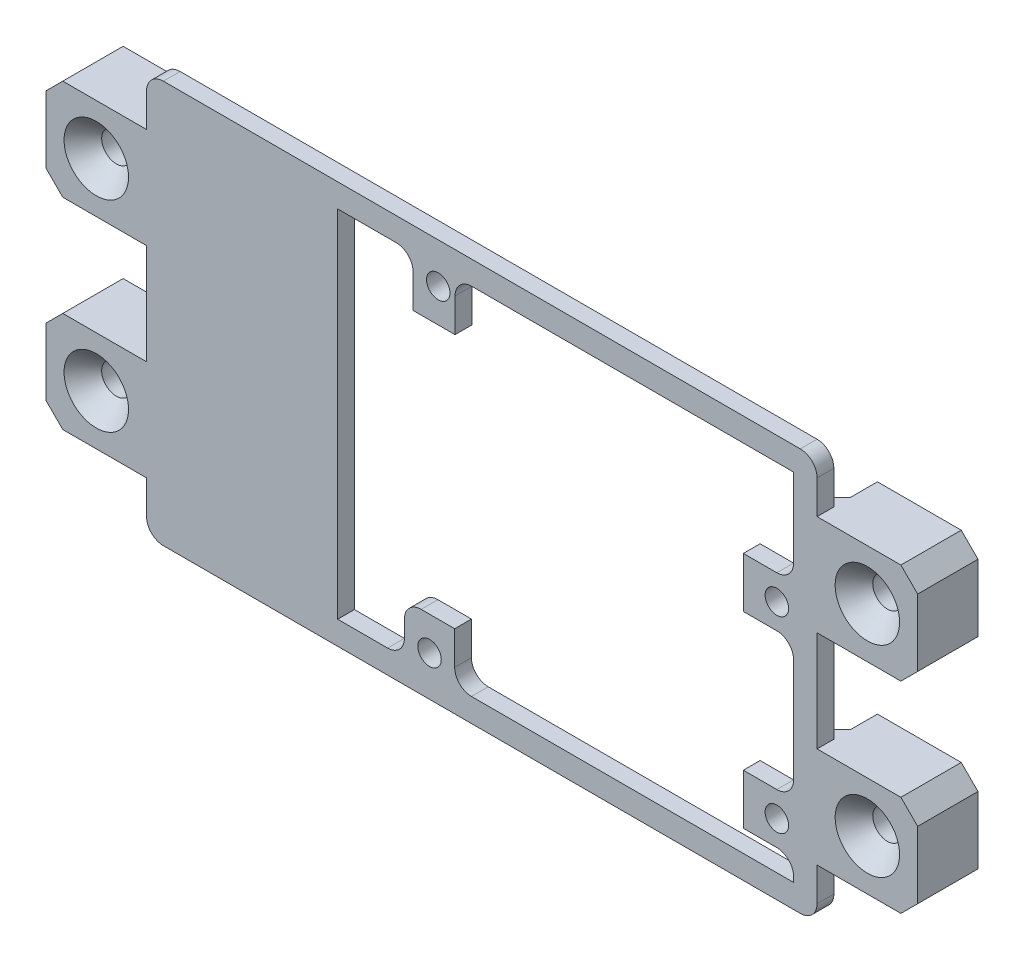
SolidWorks part; units mm, degrees
ref_plane "Front Plane" through (0, 0, 0) normal (0, 0, 1) x (1, 0, 0)
ref_plane "Top Plane" through (0, 0, 0) normal (0, 1, 0) x (1, 0, 0)
ref_plane "Right Plane" through (0, 0, 0) normal (1, 0, 0) x (0, 0, -1)
sketch "Sketch1" plane through (0, 0, 0) normal (0, 0, 1) x (1, 0, 0)
  line L1 (-62.5, 30) -> (37.5, 30)
  line L2 (-62.5, 30) -> (-62.5, -30)
  line L3 (-62.5, -30) -> (37.5, -30)
  line L4 (37.5, 30) -> (37.5, -30)
  line L7 (-34, 26.5) -> (34, 26.5)
  line L8 (-34, 26.5) -> (-34, -26.5)
  line L9 (-34, -26.5) -> (34, -26.5)
  line L10 (34, 26.5) -> (34, -26.5)
  line L11 (-34, 26.5) -> (34, -26.5) construction
  line L12 (-34, -26.5) -> (34, 26.5) construction
  line L13 (-22.75, 19) -> (-16.5, 19)
  line L14 (-22.75, 19) -> (-22.75, 26.5)
  line L15 (-22.75, 26.5) -> (-16.5, 26.5)
  line L16 (-16.5, 19) -> (-16.5, 26.5)
  line L23 (34, 12.25) -> (26.5, 12.25)
  line L24 (34, 12.25) -> (34, 4.75)
  line L29 (34, -15.75) -> (26.5, -15.75)
  line L30 (34, -15.75) -> (34, -23.25)
  line L35 (-16.55, -26.5) -> (-24.05, -26.5)
  line L36 (-16.55, -26.5) -> (-16.55, -19)
  line L37 (-16.55, -19) -> (-24.05, -19)
  line L38 (-24.05, -26.5) -> (-24.05, -19)
  line L39 (34, -23.25) -> (26.5, -23.25)
  line L40 (26.5, -15.75) -> (26.5, -23.25)
  line L41 (34, 4.75) -> (26.5, 4.75)
  line L42 (26.5, 12.25) -> (26.5, 4.75)
  circle A0 centre (-19, 24) radius 1.75
  circle A1 centre (31.5, 8.5) radius 1.75
  circle A2 centre (31.5, -19.5) radius 1.75
  circle A3 centre (-20.3, -24) radius 1.75
  point P0 (0, 0)
  point P6 (0, 0)
  point P35 (-20.3, -19)
  point P36 (26.5, -19.5)
  point P37 (26.5, 8.5)
  dimension "D5" = 3.5
  dimension "D8" = 3.5
  dimension "D9" = 3.5
  dimension "D16" = 3.5
  dimension "D1" = 100
  dimension "D2" = 60
  dimension "D3" = 68
  dimension "D4" = 53
  dimension "D6" = 15
  dimension "D7" = 50.5
  dimension "D10" = 7
  dimension "D11" = 65.5
  dimension "D12" = 35
  dimension "D13" = 6.25
  dimension "D14" = 7.5
  dimension "D15" = 7.5
  dimension "D17" = 13.7
  dimension "D18" = 2.5
  dimension "D19" = 7.5
  dimension "D20" = 7.5
  dimension "D21" = 7.5
  dimension "D22" = 7.5
  dimension "D23" = 2.5
  dimension "D24" = 7.5
  dimension "D25" = 3.5
  dimension "D26" = 3.5
extrude "Boss-Extrude1" add sketch "Sketch1" along normal blind 2.5 contours L4 L1 L2 L3 L7 L10 L9 L8 | L13 L16 L7 L14 A0 | L35 L38 L37 L9 A3 | L30 L39 L40 L10 A2 | L24 L41 L42 L10 A1
sketch "Sketch2" plane through (0, 0, 2.5) normal (0, 0, 1) x (1, 0, 0)
  line L0 (-62.5, 0) -> (-62.5, 30) construction
  line L1 (-62.5, 30) -> (-62.5, -30) construction
  line L3 (-77.5, 22.5) -> (-62.5, 22.5)
  line L4 (-77.5, 22.5) -> (-77.5, 7.5)
  line L5 (-77.5, 7.5) -> (-62.5, 7.5)
  line L6 (-62.5, 22.5) -> (-62.5, 7.5)
  point P9 (-62.5, 15)
  dimension "D1" = 15
  dimension "D2" = 15
extrude "Boss-Extrude2" add sketch "Sketch2" against normal blind 9
ref_plane "Plane1" through (-70, 0, 0) normal (-1, 0, 0) x (0, 0, 1)
sketch "Sketch3" plane through (-70, 0, 0) normal (-1, 0, 0) x (0, 0, 1)
  line L0 (2.5, 15) -> (-6.5, 15)
  line L1 (2.5, 22.5) -> (2.5, 7.5) construction
  line L2 (-6.5, 22.5) -> (-6.5, 7.5) construction
  line L3 (-6.5, 15) -> (-6.5, 12.8)
  line L4 (-6.5, 12.8) -> (-0.5, 12.8)
  line L5 (-0.5, 12.8) -> (2.5, 10.1921)
  line L6 (2.5, 10.1921) -> (2.5, 15)
  line L7 (-0.5, 12.8) -> (-0.5, 15) construction
  point P6 (0, 0)
  point P11 (-0.8121, 15)
  point P12 (0, 0)
  point P13 (-0.5054, 14.5068)
  dimension "D1" = 2.2
  dimension "D2" = 131
  dimension "D3" = 3
revolve "Cut-Revolve1" cut sketch "Sketch3" angle 360 about L0
mirror "Mirror1" about plane through (0, 0, 0) normal (0, 1, 0) of "Boss-Extrude2", "Cut-Revolve1"
ref_plane "Plane2" through (-12.5, 0, 0) normal (-1, 0, 0) x (0, 0, 1)
mirror "Mirror2" about plane through (-12.5, 0, 0) normal (-1, 0, 0) of "Mirror1", "Boss-Extrude2", "Cut-Revolve1"
fillet "Fillet1" radius 2.5 9 edges at (-24.05, -26.5, 1.25) (-24.05, -19, 1.25) (-16.55, -26.5, 1.25) (34, -23.25, 1.25) (34, -15.75, 1.25) (34, 4.75, 1.25) (34, 12.25, 1.25) (-16.5, 26.5, 1.25) (-22.75, 26.5, 1.25)
fillet "Fillet2" radius 2.5 4 edges at (37.5, -30, 1.25) (37.5, 30, 1.25) (-62.5, 30, 1.25) (-62.5, -30, 1.25)
chamfer "Chamfer1" distance 2.5 angle 45 12 edges at (-77.5, 22.5, -2) (-77.5, 7.5, -2) (-77.5, -22.5, -2) (-77.5, -7.5, -2) (-62.5, 15, 0) (-62.5, -15, 0) (52.5, -22.5, -2) (52.5, -7.5, -2) (52.5, 7.5, -2) (52.5, 22.5, -2) (37.5, -15, 0) (37.5, 15, 0)
